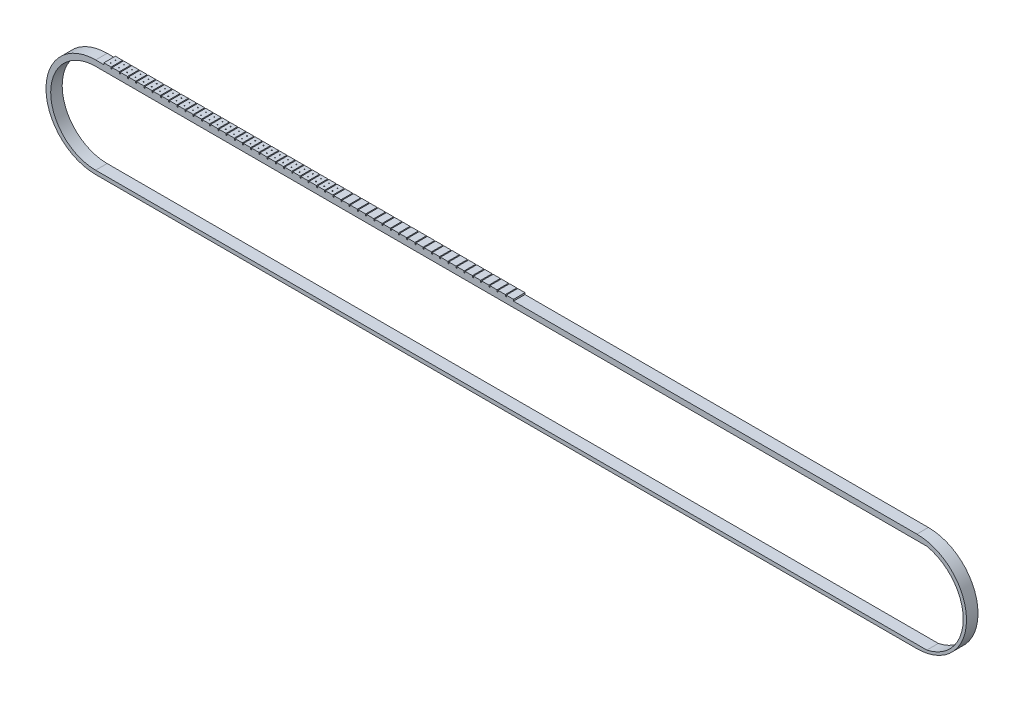
SolidWorks part; units mm, degrees
ref_plane "Front Plane" through (0, 0, 0) normal (0, 0, 1) x (1, 0, 0)
ref_plane "Top Plane" through (0, 0, 0) normal (0, 1, 0) x (1, 0, 0)
ref_plane "Right Plane" through (0, 0, 0) normal (1, 0, 0) x (0, 0, -1)
sketch "Sketch1" plane through (0, 0, 0) normal (0, 0, 1) x (1, 0, 0)
  line L0 (-2208.881, 0) -> (2791.119, 0)
  line L1 (2791.119, -604.315) -> (-2208.881, -604.315)
  arc A0 (2791.119, 0) -> (2791.119, -604.315) centre (2791.119, -302.1575) cw
  arc A1 (-2208.881, 0) -> (-2208.881, -604.315) centre (-2208.881, -302.1575) ccw
  dimension "D1" = 5000
extrude "Boss-Extrude1" add sketch "Sketch1" along normal blind 70
sketch "Sketch2" plane through (0, 0, 0) normal (0, 0, 1) x (1, 0, 0)
  line L2 (2851.7104, -33.9212) -> (-2208.881, -33.9212)
  line L3 (-2208.881, -581.1628) -> (2851.7104, -581.1628)
  arc A2 (-2208.881, -33.9212) -> (-2208.881, -581.1628) centre (-2208.881, -307.542) ccw
  arc A3 (2851.7104, -581.1628) -> (2851.7104, -33.9212) centre (2793.7566, -307.542) ccw
extrude "Cut-Extrude4" cut sketch "Sketch2" along normal through all both and the other way through all
sketch "Sketch4" plane through (0, 0, 0) normal (0, 1, 0) x (1, 0, 0)
  line L0 (2791.119, 0) -> (-2208.881, 0) construction
  line L1 (-2158.7991, 0) -> (-2114.7991, 0)
  line L2 (-2158.7991, 0) -> (-2158.7991, -70)
  line L3 (-2158.7991, -70) -> (-2114.7991, -70)
  line L4 (-2114.7991, 0) -> (-2114.7991, -70)
  line L5 (2791.119, -70) -> (-2208.881, -70) construction
  dimension "D1" = 44
extrude "Boss-Extrude2" add sketch "Sketch4" along normal blind 10 contours L4 L3 L2 L1
sketch "Sketch5" plane through (0, 0, 0) normal (0, 1, 0) x (1, 0, 0)
  line L0 (-2064.7991, 0) -> (-2108.7991, 0)
  line L1 (-2108.7991, 0) -> (-2108.7991, -70)
  line L2 (-2108.7991, -70) -> (-2064.7991, -70)
  line L3 (-2064.7991, -70) -> (-2064.7991, 0)
  line L4 (-2114.7991, 0) -> (-2158.7991, 0)
  line L5 (-2158.7991, 0) -> (-2158.7991, -70)
  line L6 (-2158.7991, -70) -> (-2114.7991, -70)
  line L7 (-2114.7991, -70) -> (-2114.7991, 0)
  line L8 (-2114.7991, 0) -> (-2158.7991, 0)
  line L9 (-2158.7991, 0) -> (-2158.7991, -70)
  line L10 (-2158.7991, -70) -> (-2114.7991, -70)
  line L11 (-2114.7991, -70) -> (-2114.7991, 0)
  line L12 (-2014.7991, 0) -> (-2058.7991, 0)
  line L13 (-2058.7991, 0) -> (-2058.7991, -70)
  line L14 (-2058.7991, -70) -> (-2014.7991, -70)
  line L15 (-2014.7991, -70) -> (-2014.7991, 0)
  line L16 (-1964.7991, 0) -> (-2008.7991, 0)
  line L17 (-2008.7991, 0) -> (-2008.7991, -70)
  line L18 (-2008.7991, -70) -> (-1964.7991, -70)
  line L19 (-1964.7991, -70) -> (-1964.7991, 0)
  line L20 (-1914.7991, 0) -> (-1958.7991, 0)
  line L21 (-1958.7991, 0) -> (-1958.7991, -70)
  line L22 (-1958.7991, -70) -> (-1914.7991, -70)
  line L23 (-1914.7991, -70) -> (-1914.7991, 0)
  line L24 (-1864.7991, 0) -> (-1908.7991, 0)
  line L25 (-1908.7991, 0) -> (-1908.7991, -70)
  line L26 (-1908.7991, -70) -> (-1864.7991, -70)
  line L27 (-1864.7991, -70) -> (-1864.7991, 0)
  line L28 (-1814.7991, 0) -> (-1858.7991, 0)
  line L29 (-1858.7991, 0) -> (-1858.7991, -70)
  line L30 (-1858.7991, -70) -> (-1814.7991, -70)
  line L31 (-1814.7991, -70) -> (-1814.7991, 0)
  line L32 (-1764.7991, 0) -> (-1808.7991, 0)
  line L33 (-1808.7991, 0) -> (-1808.7991, -70)
  line L34 (-1808.7991, -70) -> (-1764.7991, -70)
  line L35 (-1764.7991, -70) -> (-1764.7991, 0)
  line L36 (-1714.7991, 0) -> (-1758.7991, 0)
  line L37 (-1758.7991, 0) -> (-1758.7991, -70)
  line L38 (-1758.7991, -70) -> (-1714.7991, -70)
  line L39 (-1714.7991, -70) -> (-1714.7991, 0)
  line L40 (-1664.7991, 0) -> (-1708.7991, 0)
  line L41 (-1708.7991, 0) -> (-1708.7991, -70)
  line L42 (-1708.7991, -70) -> (-1664.7991, -70)
  line L43 (-1664.7991, -70) -> (-1664.7991, 0)
  line L44 (-1614.7991, 0) -> (-1658.7991, 0)
  line L45 (-1658.7991, 0) -> (-1658.7991, -70)
  line L46 (-1658.7991, -70) -> (-1614.7991, -70)
  line L47 (-1614.7991, -70) -> (-1614.7991, 0)
  line L48 (-1564.7991, 0) -> (-1608.7991, 0)
  line L49 (-1608.7991, 0) -> (-1608.7991, -70)
  line L50 (-1608.7991, -70) -> (-1564.7991, -70)
  line L51 (-1564.7991, -70) -> (-1564.7991, 0)
  line L52 (-1514.7991, 0) -> (-1558.7991, 0)
  line L53 (-1558.7991, 0) -> (-1558.7991, -70)
  line L54 (-1558.7991, -70) -> (-1514.7991, -70)
  line L55 (-1514.7991, -70) -> (-1514.7991, 0)
  line L56 (-1464.7991, 0) -> (-1508.7991, 0)
  line L57 (-1508.7991, 0) -> (-1508.7991, -70)
  line L58 (-1508.7991, -70) -> (-1464.7991, -70)
  line L59 (-1464.7991, -70) -> (-1464.7991, 0)
  line L60 (-1414.7991, 0) -> (-1458.7991, 0)
  line L61 (-1458.7991, 0) -> (-1458.7991, -70)
  line L62 (-1458.7991, -70) -> (-1414.7991, -70)
  line L63 (-1414.7991, -70) -> (-1414.7991, 0)
  line L64 (-1364.7991, 0) -> (-1408.7991, 0)
  line L65 (-1408.7991, 0) -> (-1408.7991, -70)
  line L66 (-1408.7991, -70) -> (-1364.7991, -70)
  line L67 (-1364.7991, -70) -> (-1364.7991, 0)
  line L68 (-1314.7991, 0) -> (-1358.7991, 0)
  line L69 (-1358.7991, 0) -> (-1358.7991, -70)
  line L70 (-1358.7991, -70) -> (-1314.7991, -70)
  line L71 (-1314.7991, -70) -> (-1314.7991, 0)
  line L72 (-1264.7991, 0) -> (-1308.7991, 0)
  line L73 (-1308.7991, 0) -> (-1308.7991, -70)
  line L74 (-1308.7991, -70) -> (-1264.7991, -70)
  line L75 (-1264.7991, -70) -> (-1264.7991, 0)
  line L76 (-1214.7991, 0) -> (-1258.7991, 0)
  line L77 (-1258.7991, 0) -> (-1258.7991, -70)
  line L78 (-1258.7991, -70) -> (-1214.7991, -70)
  line L79 (-1214.7991, -70) -> (-1214.7991, 0)
  line L80 (-1164.7991, 0) -> (-1208.7991, 0)
  line L81 (-1208.7991, 0) -> (-1208.7991, -70)
  line L82 (-1208.7991, -70) -> (-1164.7991, -70)
  line L83 (-1164.7991, -70) -> (-1164.7991, 0)
  line L84 (-1114.7991, 0) -> (-1158.7991, 0)
  line L85 (-1158.7991, 0) -> (-1158.7991, -70)
  line L86 (-1158.7991, -70) -> (-1114.7991, -70)
  line L87 (-1114.7991, -70) -> (-1114.7991, 0)
  line L88 (-1064.7991, 0) -> (-1108.7991, 0)
  line L89 (-1108.7991, 0) -> (-1108.7991, -70)
  line L90 (-1108.7991, -70) -> (-1064.7991, -70)
  line L91 (-1064.7991, -70) -> (-1064.7991, 0)
  line L92 (-1014.7991, 0) -> (-1058.7991, 0)
  line L93 (-1058.7991, 0) -> (-1058.7991, -70)
  line L94 (-1058.7991, -70) -> (-1014.7991, -70)
  line L95 (-1014.7991, -70) -> (-1014.7991, 0)
  line L96 (-964.7991, 0) -> (-1008.7991, 0)
  line L97 (-1008.7991, 0) -> (-1008.7991, -70)
  line L98 (-1008.7991, -70) -> (-964.7991, -70)
  line L99 (-964.7991, -70) -> (-964.7991, 0)
  line L100 (-914.7991, 0) -> (-958.7991, 0)
  line L101 (-958.7991, 0) -> (-958.7991, -70)
  line L102 (-958.7991, -70) -> (-914.7991, -70)
  line L103 (-914.7991, -70) -> (-914.7991, 0)
  line L104 (-864.7991, 0) -> (-908.7991, 0)
  line L105 (-908.7991, 0) -> (-908.7991, -70)
  line L106 (-908.7991, -70) -> (-864.7991, -70)
  line L107 (-864.7991, -70) -> (-864.7991, 0)
  line L108 (-814.7991, 0) -> (-858.7991, 0)
  line L109 (-858.7991, 0) -> (-858.7991, -70)
  line L110 (-858.7991, -70) -> (-814.7991, -70)
  line L111 (-814.7991, -70) -> (-814.7991, 0)
  line L112 (-764.7991, 0) -> (-808.7991, 0)
  line L113 (-808.7991, 0) -> (-808.7991, -70)
  line L114 (-808.7991, -70) -> (-764.7991, -70)
  line L115 (-764.7991, -70) -> (-764.7991, 0)
  line L116 (-714.7991, 0) -> (-758.7991, 0)
  line L117 (-758.7991, 0) -> (-758.7991, -70)
  line L118 (-758.7991, -70) -> (-714.7991, -70)
  line L119 (-714.7991, -70) -> (-714.7991, 0)
  line L120 (-664.7991, 0) -> (-708.7991, 0)
  line L121 (-708.7991, 0) -> (-708.7991, -70)
  line L122 (-708.7991, -70) -> (-664.7991, -70)
  line L123 (-664.7991, -70) -> (-664.7991, 0)
  line L124 (-614.7991, 0) -> (-658.7991, 0)
  line L125 (-658.7991, 0) -> (-658.7991, -70)
  line L126 (-658.7991, -70) -> (-614.7991, -70)
  line L127 (-614.7991, -70) -> (-614.7991, 0)
  line L128 (-564.7991, 0) -> (-608.7991, 0)
  line L129 (-608.7991, 0) -> (-608.7991, -70)
  line L130 (-608.7991, -70) -> (-564.7991, -70)
  line L131 (-564.7991, -70) -> (-564.7991, 0)
  line L132 (-514.7991, 0) -> (-558.7991, 0)
  line L133 (-558.7991, 0) -> (-558.7991, -70)
  line L134 (-558.7991, -70) -> (-514.7991, -70)
  line L135 (-514.7991, -70) -> (-514.7991, 0)
  line L136 (-464.7991, 0) -> (-508.7991, 0)
  line L137 (-508.7991, 0) -> (-508.7991, -70)
  line L138 (-508.7991, -70) -> (-464.7991, -70)
  line L139 (-464.7991, -70) -> (-464.7991, 0)
  line L140 (-414.7991, 0) -> (-458.7991, 0)
  line L141 (-458.7991, 0) -> (-458.7991, -70)
  line L142 (-458.7991, -70) -> (-414.7991, -70)
  line L143 (-414.7991, -70) -> (-414.7991, 0)
  line L144 (-364.7991, 0) -> (-408.7991, 0)
  line L145 (-408.7991, 0) -> (-408.7991, -70)
  line L146 (-408.7991, -70) -> (-364.7991, -70)
  line L147 (-364.7991, -70) -> (-364.7991, 0)
  line L148 (-314.7991, 0) -> (-358.7991, 0)
  line L149 (-358.7991, 0) -> (-358.7991, -70)
  line L150 (-358.7991, -70) -> (-314.7991, -70)
  line L151 (-314.7991, -70) -> (-314.7991, 0)
  line L152 (-264.7991, 0) -> (-308.7991, 0)
  line L153 (-308.7991, 0) -> (-308.7991, -70)
  line L154 (-308.7991, -70) -> (-264.7991, -70)
  line L155 (-264.7991, -70) -> (-264.7991, 0)
  line L156 (-214.7991, 0) -> (-258.7991, 0)
  line L157 (-258.7991, 0) -> (-258.7991, -70)
  line L158 (-258.7991, -70) -> (-214.7991, -70)
  line L159 (-214.7991, -70) -> (-214.7991, 0)
  line L160 (-164.7991, 0) -> (-208.7991, 0)
  line L161 (-208.7991, 0) -> (-208.7991, -70)
  line L162 (-208.7991, -70) -> (-164.7991, -70)
  line L163 (-164.7991, -70) -> (-164.7991, 0)
  line L164 (-114.7991, 0) -> (-158.7991, 0)
  line L165 (-158.7991, 0) -> (-158.7991, -70)
  line L166 (-158.7991, -70) -> (-114.7991, -70)
  line L167 (-114.7991, -70) -> (-114.7991, 0)
  line L168 (-64.7991, 0) -> (-108.7991, 0)
  line L169 (-108.7991, 0) -> (-108.7991, -70)
  line L170 (-108.7991, -70) -> (-64.7991, -70)
  line L171 (-64.7991, -70) -> (-64.7991, 0)
  line L172 (-14.7991, 0) -> (-58.7991, 0)
  line L173 (-58.7991, 0) -> (-58.7991, -70)
  line L174 (-58.7991, -70) -> (-14.7991, -70)
  line L175 (-14.7991, -70) -> (-14.7991, 0)
  line L176 (35.2009, 0) -> (-8.7991, 0)
  line L177 (-8.7991, 0) -> (-8.7991, -70)
  line L178 (-8.7991, -70) -> (35.2009, -70)
  line L179 (35.2009, -70) -> (35.2009, 0)
  line L180 (85.2009, 0) -> (41.2009, 0)
  line L181 (41.2009, 0) -> (41.2009, -70)
  line L182 (41.2009, -70) -> (85.2009, -70)
  line L183 (85.2009, -70) -> (85.2009, 0)
  line L184 (135.2009, 0) -> (91.2009, 0)
  line L185 (91.2009, 0) -> (91.2009, -70)
  line L186 (91.2009, -70) -> (135.2009, -70)
  line L187 (135.2009, -70) -> (135.2009, 0)
  line L188 (185.2009, 0) -> (141.2009, 0)
  line L189 (141.2009, 0) -> (141.2009, -70)
  line L190 (141.2009, -70) -> (185.2009, -70)
  line L191 (185.2009, -70) -> (185.2009, 0)
  line L192 (235.2009, 0) -> (191.2009, 0)
  line L193 (191.2009, 0) -> (191.2009, -70)
  line L194 (191.2009, -70) -> (235.2009, -70)
  line L195 (235.2009, -70) -> (235.2009, 0)
  line L196 (285.2009, 0) -> (241.2009, 0)
  line L197 (241.2009, 0) -> (241.2009, -70)
  line L198 (241.2009, -70) -> (285.2009, -70)
  line L199 (285.2009, -70) -> (285.2009, 0)
  line L200 (335.2009, 0) -> (291.2009, 0)
  line L201 (291.2009, 0) -> (291.2009, -70)
  line L202 (291.2009, -70) -> (335.2009, -70)
  line L203 (335.2009, -70) -> (335.2009, 0)
  line L204 (-2114.7991, 0) -> (-2064.7991, 0) construction
  dimension "D3" = 50
  dimension "D1" = 0
  dimension "D2" = 50
extrude "Boss-Extrude3" add sketch "Sketch5" along normal blind 10
sketch "Sketch6" plane through (0, 0, 0) normal (0, 1, 0) x (1, 0, 0)
  line L0 (-2136.7991, 0) -> (-2136.7991, -70)
  line L1 (-2158.7991, 0) -> (-2114.7991, 0) construction
  line L2 (-2158.7991, -70) -> (-2114.7991, -70) construction
  line L3 (-2136.7991, -20) -> (-2086.7991, -20) construction
  line L5 (-2208.881, -35) -> (-2114.7991, -35)
  line L6 (-2208.881, -70) -> (-2208.881, 0) construction
  line L7 (-2114.7991, 0) -> (-2114.7991, -70) construction
  circle A0 centre (-2136.7991, -20) radius 2.5
  circle A1 centre (-2136.7991, -50) radius 2.5
  circle A2 centre (-2086.7991, -20) radius 2.5
  circle A3 centre (-2086.7991, -50) radius 2.5
  circle A4 centre (-2036.7991, -20) radius 2.5
  circle A5 centre (-2036.7991, -50) radius 2.5
  circle A6 centre (-1986.7991, -20) radius 2.5
  circle A7 centre (-1986.7991, -50) radius 2.5
  circle A8 centre (-1936.7991, -20) radius 2.5
  circle A9 centre (-1936.7991, -50) radius 2.5
  circle A10 centre (-1886.7991, -20) radius 2.5
  circle A11 centre (-1886.7991, -50) radius 2.5
  circle A12 centre (-1836.7991, -20) radius 2.5
  circle A13 centre (-1836.7991, -50) radius 2.5
  circle A14 centre (-1786.7991, -20) radius 2.5
  circle A15 centre (-1786.7991, -50) radius 2.5
  circle A16 centre (-1736.7991, -20) radius 2.5
  circle A17 centre (-1736.7991, -50) radius 2.5
  circle A18 centre (-1686.7991, -20) radius 2.5
  circle A19 centre (-1686.7991, -50) radius 2.5
  circle A20 centre (-1636.7991, -20) radius 2.5
  circle A21 centre (-1636.7991, -50) radius 2.5
  circle A22 centre (-1586.7991, -20) radius 2.5
  circle A23 centre (-1586.7991, -50) radius 2.5
  circle A24 centre (-1536.7991, -20) radius 2.5
  circle A25 centre (-1536.7991, -50) radius 2.5
  circle A26 centre (-1486.7991, -20) radius 2.5
  circle A27 centre (-1486.7991, -50) radius 2.5
  circle A28 centre (-1436.7991, -20) radius 2.5
  circle A29 centre (-1436.7991, -50) radius 2.5
  circle A30 centre (-1386.7991, -20) radius 2.5
  circle A31 centre (-1386.7991, -50) radius 2.5
  circle A32 centre (-1336.7991, -20) radius 2.5
  circle A33 centre (-1336.7991, -50) radius 2.5
  circle A34 centre (-1286.7991, -20) radius 2.5
  circle A35 centre (-1286.7991, -50) radius 2.5
  circle A36 centre (-1236.7991, -20) radius 2.5
  circle A37 centre (-1236.7991, -50) radius 2.5
  circle A38 centre (-1186.7991, -20) radius 2.5
  circle A39 centre (-1186.7991, -50) radius 2.5
  circle A40 centre (-1136.7991, -20) radius 2.5
  circle A41 centre (-1136.7991, -50) radius 2.5
  circle A42 centre (-1086.7991, -20) radius 2.5
  circle A43 centre (-1086.7991, -50) radius 2.5
  circle A44 centre (-1036.7991, -20) radius 2.5
  circle A45 centre (-1036.7991, -50) radius 2.5
  circle A46 centre (-986.7991, -20) radius 2.5
  circle A47 centre (-986.7991, -50) radius 2.5
  circle A48 centre (-936.7991, -20) radius 2.5
  circle A49 centre (-936.7991, -50) radius 2.5
  circle A50 centre (-886.7991, -20) radius 2.5
  circle A51 centre (-886.7991, -50) radius 2.5
  circle A52 centre (-836.7991, -20) radius 2.5
  circle A53 centre (-836.7991, -50) radius 2.5
  circle A54 centre (-786.7991, -20) radius 2.5
  circle A55 centre (-786.7991, -50) radius 2.5
  circle A56 centre (-736.7991, -20) radius 2.5
  circle A57 centre (-736.7991, -50) radius 2.5
  circle A58 centre (-686.7991, -20) radius 2.5
  circle A59 centre (-686.7991, -50) radius 2.5
  circle A60 centre (-636.7991, -20) radius 2.5
  circle A61 centre (-636.7991, -50) radius 2.5
  circle A62 centre (-586.7991, -20) radius 2.5
  circle A63 centre (-586.7991, -50) radius 2.5
  circle A64 centre (-536.7991, -20) radius 2.5
  circle A65 centre (-536.7991, -50) radius 2.5
  circle A66 centre (-486.7991, -20) radius 2.5
  circle A67 centre (-486.7991, -50) radius 2.5
  circle A68 centre (-436.7991, -20) radius 2.5
  circle A69 centre (-436.7991, -50) radius 2.5
  circle A70 centre (-386.7991, -20) radius 2.5
  circle A71 centre (-386.7991, -50) radius 2.5
  circle A72 centre (-336.7991, -20) radius 2.5
  circle A73 centre (-336.7991, -50) radius 2.5
  circle A74 centre (-286.7991, -20) radius 2.5
  circle A75 centre (-286.7991, -50) radius 2.5
  circle A76 centre (-236.7991, -20) radius 2.5
  circle A77 centre (-236.7991, -50) radius 2.5
  circle A78 centre (-186.7991, -20) radius 2.5
  circle A79 centre (-186.7991, -50) radius 2.5
  circle A80 centre (-136.7991, -20) radius 2.5
  circle A81 centre (-136.7991, -50) radius 2.5
  circle A82 centre (-86.7991, -20) radius 2.5
  circle A83 centre (-86.7991, -50) radius 2.5
  circle A84 centre (-36.7991, -20) radius 2.5
  circle A85 centre (-36.7991, -50) radius 2.5
  circle A86 centre (13.2009, -20) radius 2.5
  circle A87 centre (13.2009, -50) radius 2.5
  circle A88 centre (63.2009, -20) radius 2.5
  circle A89 centre (63.2009, -50) radius 2.5
  circle A90 centre (113.2009, -20) radius 2.5
  circle A91 centre (113.2009, -50) radius 2.5
  circle A92 centre (163.2009, -20) radius 2.5
  circle A93 centre (163.2009, -50) radius 2.5
  circle A94 centre (213.2009, -20) radius 2.5
  circle A95 centre (213.2009, -50) radius 2.5
  circle A96 centre (263.2009, -20) radius 2.5
  circle A97 centre (263.2009, -50) radius 2.5
  circle A98 centre (313.2009, -20) radius 2.5
  circle A99 centre (313.2009, -50) radius 2.5
  dimension "D1" = 5
  dimension "D2" = 15
  dimension "D3" = 15
  dimension "D5" = 50
  dimension "D4" = 50
extrude "Cut-Extrude5" cut sketch "Sketch6" along normal through all and the other way blind 60 contours A0 | A1 | A2 | A3 | A4 | A5 | A6 | A7 | A8 | A9 | A10 | A11 | A12 | A13 | A14 | A15 | A16 | A17 | A18 | A19 | A20 | A21 | A22 | A23 | A24 | A25 | A26 | A27 | A28 | A29 | A31 | A30 | A32 | A33 | A34 | A35 | A37 | A36 | A38 | A39 | A40 | A41 | A42 | A43 | A44 | A45 | A46 | A47 | A48 | A49 | A50 | A51 | A52 | A53 | A54 | A55
